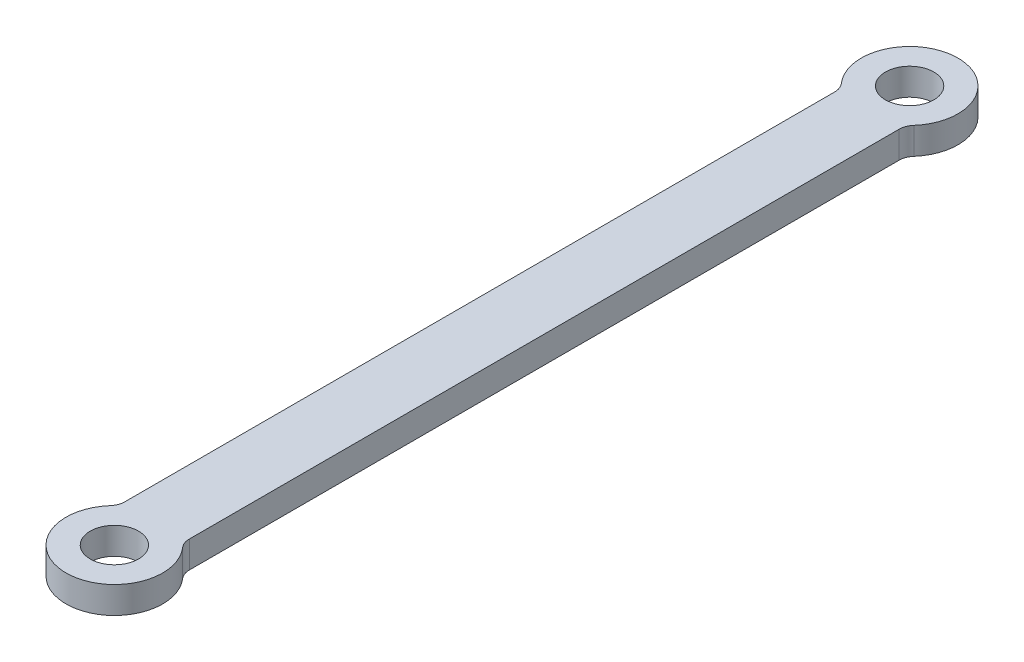
SolidWorks part; units mm, degrees
ref_plane "前视基准面" through (0, 0, 0) normal (0, 0, 1) x (1, 0, 0)
ref_plane "上视基准面" through (0, 0, 0) normal (0, 1, 0) x (1, 0, 0)
ref_plane "右视基准面" through (0, 0, 0) normal (1, 0, 0) x (0, 0, -1)
sketch "草图1" plane through (0, 0, 0) normal (0, 1, 0) x (1, 0, 0)
  line L0 (-85.4309, 43.5018) -> (-85.4309, -88.6237)
  line L5 (-73.4309, -88.6237) -> (-73.4309, 43.5018)
  arc A0 (-72.6809, 45.4861) -> (-86.1809, 45.4861) centre (-79.4309, 51.439) ccw
  circle A1 centre (-79.4309, 51.439) radius 4.5
  arc A2 (-86.1809, -90.608) -> (-72.6809, -90.608) centre (-79.4309, -96.561) ccw
  circle A3 centre (-79.4309, -96.561) radius 4.5
  arc A4 (-85.4309, 43.5018) -> (-86.1809, 45.4861) centre (-88.4309, 43.5018) ccw
  arc A5 (-73.4309, 43.5018) -> (-72.6809, 45.4861) centre (-70.4309, 43.5018) cw
  arc A6 (-85.4309, -88.6237) -> (-86.1809, -90.608) centre (-88.4309, -88.6237) cw
  arc A7 (-73.4309, -88.6237) -> (-72.6809, -90.608) centre (-70.4309, -88.6237) ccw
  dimension "D4" = 3
  dimension "D1" = 3
  dimension "D2" = 3
  dimension "D3" = 3
extrude "凸台-拉伸1" add sketch "草图1" along normal blind 5
